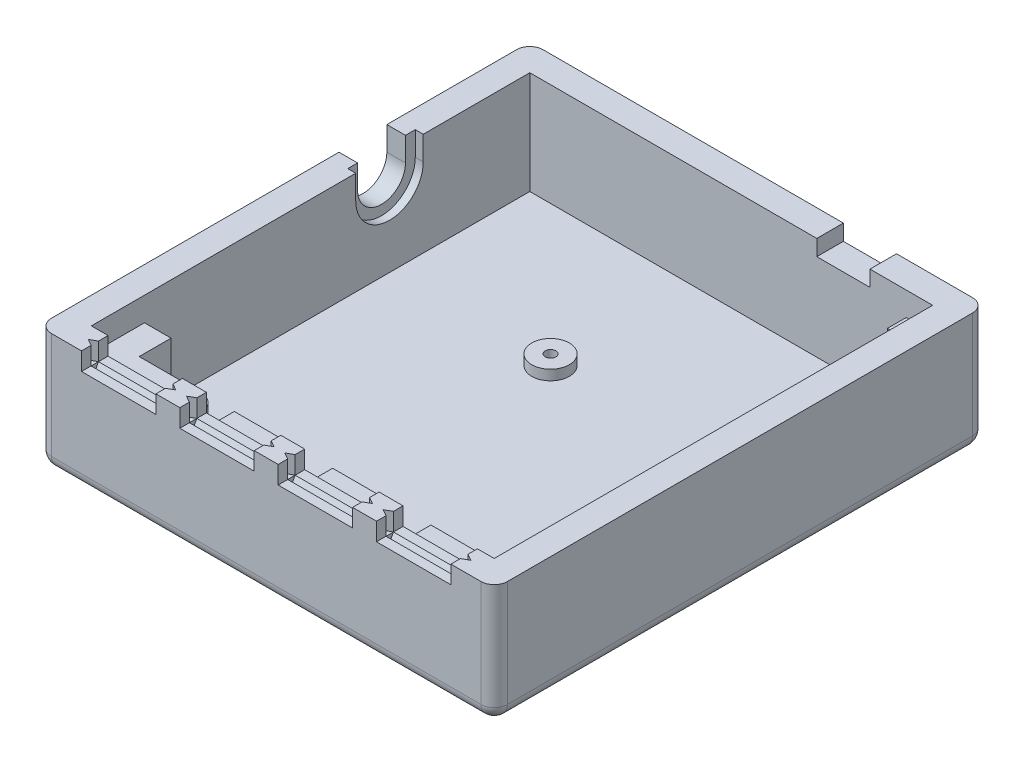
SolidWorks part; units mm, degrees
ref_plane "Front Plane" through (0, 0, 0) normal (0, 0, 1) x (1, 0, 0)
ref_plane "Top Plane" through (0, 0, 0) normal (0, 1, 0) x (1, 0, 0)
ref_plane "Right Plane" through (0, 0, 0) normal (1, 0, 0) x (0, 0, -1)
sketch "Sketch1" plane through (0, 0, 0) normal (0, 1, 0) x (1, 0, 0)
  line L0 (5, 4) -> (5, 10)
  line L1 (5, 10) -> (0, 10)
  line L2 (0, 10) -> (0, 82.5)
  line L3 (0, 82.5) -> (70.8, 82.5)
  line L4 (70.8, 82.5) -> (70.8, 79)
  line L5 (70.8, 79) -> (75.8, 79)
  line L6 (75.8, 79) -> (75.8, 4)
  line L7 (5, 4) -> (15.9, 4)
  line L8 (15.9, 4) -> (15.9, 0)
  line L9 (15.9, 0) -> (22.9, 0)
  line L10 (22.9, 0) -> (22.9, 4)
  line L11 (22.9, 4) -> (34.4, 4)
  line L12 (34.4, 4) -> (34.4, 0)
  line L13 (34.4, 0) -> (41.4, 0)
  line L14 (41.4, 0) -> (41.4, 4)
  line L15 (41.4, 4) -> (52.9, 4)
  line L16 (52.9, 4) -> (52.9, 0)
  line L17 (52.9, 0) -> (59.9, 0)
  line L18 (59.9, 0) -> (59.9, 4)
  line L19 (59.9, 4) -> (75.8, 4)
  line L20 (19.4, 27.0002) -> (19.4, -18.5168) construction
  line L21 (37.9, 24.8892) -> (37.9, -19.4403) construction
  line L22 (56.4, 24.8892) -> (56.4, -19.4529) construction
  line L23 (-5, 87.5) -> (-5, -5)
  line L24 (-5, -5) -> (80.8, -5)
  line L25 (80.8, -5) -> (80.8, 87.5)
  line L26 (80.8, 87.5) -> (-5, 87.5)
  dimension "D1" = 82.5
  dimension "D2" = 75.8
  dimension "D3" = 3.5
  dimension "D4" = 5
  dimension "D5" = 7
  dimension "D6" = 7
  dimension "D7" = 7
  dimension "D8" = 19.4
  dimension "D9" = 18.5
  dimension "D10" = 18.5
  dimension "D11" = 5
  dimension "D12" = 4
  dimension "D13" = 6
  dimension "D14" = 5
  dimension "D15" = 5
  dimension "D16" = 5
  dimension "D17" = 5
extrude "Boss-Extrude1" add sketch "Sketch1" along normal blind 14.859
sketch "Sketch2" plane through (0, 0, 0) normal (0, 1, 0) x (1, 0, 0)
  line L0 (-5, 87.5) -> (-5, -5) construction
  line L1 (-5, 87.5) -> (80.8, 87.5)
  line L2 (-5, 87.5) -> (-5, -5)
  line L3 (-5, -5) -> (80.8, -5)
  line L4 (80.8, 87.5) -> (80.8, -5)
  line L5 (80.8, 87.5) -> (-5, 87.5) construction
  line L6 (80.8, -5) -> (80.8, 87.5) construction
  line L7 (-5, -5) -> (80.8, -5) construction
  circle A0 centre (3.5, 13.5) radius 1
  circle A1 centre (19.4, 3.5) radius 1
  circle A2 centre (37.9, 3.5) radius 1
  circle A3 centre (56.4, 3.5) radius 1
  circle A4 centre (30.3, 56.1) radius 1
  circle A5 centre (71.8, 75.5) radius 1
  dimension "D3" = 2
  dimension "D1" = 3.5
  dimension "D2" = 13.5
  dimension "D4" = 19.4
  dimension "D5" = 18.5
  dimension "D6" = 18.5
  dimension "D7" = 3.5
  dimension "D8" = 56.1
  dimension "D9" = 30.3
  dimension "D10" = 71.8
  dimension "D11" = 75.5
extrude "Boss-Extrude2" add sketch "Sketch2" against normal blind 3.175
ref_plane "Plane1" through (0, 14.859, 0) normal (0, 1, 0) x (1, 0, 0)
sketch "Sketch4" plane through (0, 14.859, 0) normal (0, 1, 0) x (1, 0, 0)
  line L1 (0, 0) -> (75.8, 0)
  line L2 (0, 0) -> (0, 82.5)
  line L3 (0, 82.5) -> (75.8, 82.5)
  line L4 (75.8, 0) -> (75.8, 82.5)
  line L5 (-5, -5) -> (80.8, -5)
  line L6 (-5, -5) -> (-5, 87.5)
  line L7 (-5, 87.5) -> (80.8, 87.5)
  line L8 (80.8, -5) -> (80.8, 87.5)
  dimension "D1" = 82.5
  dimension "D2" = 75.8
  dimension "D3" = 5
  dimension "D4" = 5
  dimension "D5" = 5
  dimension "D6" = 5
extrude "Boss-Extrude3" add sketch "Sketch4" along normal blind 4.5
sketch "Sketch3" plane through (0, 0, 0) normal (1, 0, 0) x (0, 0, -1)
  line L0 (60.6, 14.859) -> (60.6, 19.359)
  line L1 (87.5, 19.359) -> (-5, 19.359) construction
  line L2 (51.6, 14.859) -> (51.6, 19.359)
  line L3 (60.6, 19.359) -> (51.6, 19.359)
  circle A0 centre (56.1, 14.859) radius 4.5 construction
  arc A1 (60.6, 14.859) -> (51.6, 14.859) centre (56.1, 14.859) cw
  dimension "D1" = 9
  dimension "D2" = 56.1
  dimension "D3" = 14.859
extrude "Cut-Extrude1" cut sketch "Sketch3" against normal through all
sketch "Sketch5" plane through (0, 0, 0) normal (0, 0, 1) x (1, 0, 0)
  line L1 (3.15, 24) -> (17.15, 24)
  line L2 (3.15, 24) -> (3.15, 16)
  line L3 (3.15, 16) -> (17.15, 16)
  line L4 (17.15, 24) -> (17.15, 16)
  line L5 (21.65, 24) -> (35.65, 24)
  line L6 (21.65, 24) -> (21.65, 16)
  line L7 (21.65, 16) -> (35.65, 16)
  line L8 (35.65, 24) -> (35.65, 16)
  line L9 (40.15, 24) -> (54.15, 24)
  line L10 (40.15, 24) -> (40.15, 16)
  line L11 (40.15, 16) -> (54.15, 16)
  line L12 (54.15, 24) -> (54.15, 16)
  line L13 (72.65, 24) -> (58.65, 24)
  line L14 (72.65, 24) -> (72.65, 16)
  line L15 (72.65, 16) -> (58.65, 16)
  line L16 (58.65, 24) -> (58.65, 16)
  point P16 (10.15, 16)
  point P17 (28.65, 16)
  point P18 (47.15, 16)
  point P19 (65.65, 16)
  dimension "D1" = 10.15
  dimension "D2" = 18.5
  dimension "D3" = 18.5
  dimension "D4" = 18.5
  dimension "D5" = 14
  dimension "D6" = 14
  dimension "D7" = 14
  dimension "D8" = 14
  dimension "D9" = 16
  dimension "D10" = 8
extrude "Cut-Extrude2" cut sketch "Sketch5" along normal through all
sketch "Sketch6" plane through (0, 0, 0) normal (0, 0, 1) x (1, 0, 0)
  line L1 (54, 16.383) -> (64, 16.383)
  line L4 (64, 16.383) -> (64, 22.383)
  line L5 (64, 22.383) -> (54, 22.383)
  line L6 (54, 22.383) -> (54, 16.383)
  point P0 (59, 16.383)
  dimension "D1" = 59
  dimension "D2" = 10
  dimension "D3" = 6
  dimension "D4" = 16.383
extrude "Cut-Extrude3" cut sketch "Sketch6" against normal through all
sketch "Sketch7" plane through (0, 0, 0) normal (0, 1, 0) x (1, 0, 0)
  line L0 (0, 13.5) -> (0, 10)
  line L1 (0, 51.6) -> (0, 0) construction
  line L2 (0, 10) -> (3.5, 10)
  line L3 (0, 10) -> (5, 10) construction
  line L4 (15.9, 3.5) -> (15.9, 0)
  line L5 (15.9, 4) -> (15.9, 0) construction
  line L6 (15.9, 0) -> (22.9, 0)
  line L7 (22.9, 0) -> (22.9, 3.5)
  line L8 (22.9, 0) -> (22.9, 4) construction
  line L9 (34.4, 3.5) -> (34.4, 0)
  line L10 (34.4, 4) -> (34.4, 0) construction
  line L11 (21.65, 0) -> (35.65, 0) construction
  line L12 (22.9, 0) -> (34.4, 0) construction
  line L13 (34.4, 0) -> (41.4, 0)
  line L14 (41.4, 0) -> (41.4, 3.5)
  line L15 (41.4, 0) -> (41.4, 4) construction
  line L16 (52.9, 3.5) -> (52.9, 0)
  line L17 (52.9, 4) -> (52.9, 0) construction
  line L18 (52.9, 0) -> (59.9, 0)
  line L19 (59.9, 0) -> (59.9, 3.5)
  line L20 (59.9, 0) -> (59.9, 4) construction
  line L21 (75.8, 79) -> (69.8635, 79)
  line L22 (75.8, 79) -> (70.8, 79) construction
  line L23 (75.8, 79) -> (75.8, 75.5)
  line L24 (75.8, 0) -> (75.8, 82.5) construction
  circle A0 centre (30.3, 56.1) radius 3.54
  circle A1 centre (30.3, 56.1) radius 1
  circle A2 centre (3.5, 13.5) radius 1
  arc A3 (0, 13.5) -> (3.5, 10) centre (3.5, 13.5) cw
  circle A4 centre (19.4, 3.5) radius 1
  arc A5 (15.9, 3.5) -> (22.9, 3.5) centre (19.4, 3.5) cw
  circle A6 centre (37.9, 3.5) radius 1
  arc A7 (34.4, 3.5) -> (41.4, 3.5) centre (37.9, 3.5) cw
  circle A8 centre (56.4, 3.5) radius 1
  arc A9 (52.9, 3.5) -> (59.9, 3.5) centre (56.4, 3.5) cw
  circle A10 centre (71.8, 75.5) radius 1
  arc A11 (75.8, 75.5) -> (69.8635, 79) centre (71.8, 75.5) cw
  dimension "D1" = 2.54
  dimension "D2" = 2
  dimension "D3" = 2
  dimension "D4" = 2
  dimension "D5" = 2
  dimension "D7" = 2
  dimension "D9" = 2
extrude "Boss-Extrude4" add sketch "Sketch7" along normal blind 1.9
fillet "Fillet1" radius 2.5 1 edges at (-5, 8.092, 5)
fillet "Fillet2" radius 2.5 1 edges at (80.8, 8.092, 5)
fillet "Fillet3" radius 2.5 1 edges at (80.8, 8.092, -87.5)
fillet "Fillet4" radius 2.5 1 edges at (-5, 8.092, -87.5)
fillet "Fillet5" radius 2.5 8 edges at (80.0678, -3.175, 4.2678) (37.9, -3.175, 5) (-4.2678, -3.175, 4.2678) (-5, -3.175, -41.25) (-4.2678, -3.175, -86.7678) (37.9, -3.175, -87.5) (80.0678, -3.175, -86.7678) (80.8, -3.175, -41.25)
sketch "Sketch8" plane through (0, 0, 0) normal (1, 0, 0) x (0, 0, -1)
  line L0 (62.45, 14.855) -> (62.45, 21.205)
  line L1 (49.75, 14.855) -> (49.75, 21.205)
  line L2 (49.75, 21.205) -> (62.45, 21.205)
  circle A0 centre (56.1, 14.855) radius 6.35 construction
  arc A1 (49.75, 14.855) -> (62.45, 14.855) centre (56.1, 14.855) ccw
  dimension "D3" = 12.7
  dimension "D1" = 56.1
  dimension "D2" = 14.855
extrude "Cut-Extrude4" cut sketch "Sketch8" against normal blind 1.5
ref_plane "Plane2" through (0, 19.359, 0) normal (0, 1, 0) x (1, 0, 0)
sketch "Sketch9" plane through (0, 19.359, 0) normal (0, 1, 0) x (1, 0, 0)
  line L0 (3.15, -5) -> (3.15, 0) construction
  line L1 (3.15, -1.8) -> (3.15, -3.2)
  line L2 (3.15, 0) -> (3.15, -5) construction
  line L3 (3.15, -3.2) -> (1.9, -2.5)
  line L4 (1.9, -2.5) -> (3.15, -1.8)
  line L5 (17.15, -1.8) -> (17.15, -3.2)
  line L6 (17.15, -5) -> (17.15, 0) construction
  line L7 (17.15, -3.2) -> (18.4, -2.5)
  line L8 (18.4, -2.5) -> (17.15, -1.8)
  line L9 (21.65, -1.8) -> (21.65, -3.2)
  line L10 (21.65, 0) -> (21.65, -5) construction
  line L11 (21.65, -3.2) -> (20.4, -2.5)
  line L12 (20.4, -2.5) -> (21.65, -1.8)
  line L13 (35.65, -1.8) -> (36.9, -2.5)
  line L14 (35.65, -5) -> (35.65, 0) construction
  line L15 (36.9, -2.5) -> (35.65, -3.2)
  line L16 (35.65, -5) -> (35.65, 0) construction
  line L17 (35.65, -3.2) -> (35.65, -1.8)
  line L18 (40.15, -1.8) -> (38.9, -2.5)
  line L19 (40.15, -5) -> (40.15, 0) construction
  line L20 (38.9, -2.5) -> (40.15, -3.2)
  line L21 (40.15, -3.2) -> (40.15, -1.8)
  line L22 (54.15, -1.8) -> (54.15, -3.2)
  line L23 (54.15, -5) -> (54.15, 0) construction
  line L24 (54.15, -3.2) -> (55.4, -2.5)
  line L25 (55.4, -2.5) -> (54.15, -1.8)
  line L26 (58.65, -1.8) -> (58.65, -3.2)
  line L27 (58.65, -5) -> (58.65, 0) construction
  line L28 (58.65, -3.2) -> (57.4, -2.5)
  line L29 (57.4, -2.5) -> (58.65, -1.8)
  line L30 (72.65, -1.8) -> (72.65, -3.2)
  line L31 (72.65, -5) -> (72.65, 0) construction
  line L32 (72.65, -5) -> (72.65, 0) construction
  line L33 (72.65, -3.2) -> (73.9, -2.5)
  line L34 (73.9, -2.5) -> (72.65, -1.8)
  point P0 (3.15, -2.5)
  dimension "D1" = 1.25
  dimension "D2" = 0.7
  dimension "D3" = 0.7
  dimension "D4" = 1.25
  dimension "D5" = 1.25
  dimension "D6" = 1.25
  dimension "D7" = 1.25
  dimension "D8" = 1.25
  dimension "D9" = 1.25
  dimension "D10" = 1.25
extrude "Cut-Extrude5" cut sketch "Sketch9" against normal blind 4
sketch "Sketch10" plane through (0, 0, 0) normal (1, 0, 0) x (0, 0, -1)
  line L0 (-3.2, 16) -> (-1.8, 16)
  line L1 (-1.8, 16) -> (-2.5, 14.7)
  line L2 (-2.5, 14.7) -> (-3.2, 16)
  line L3 (-2.5, 16) -> (-2.5, 14.7) construction
  point P4 (0, 0)
  dimension "D1" = 16
  dimension "D2" = 2.5
  dimension "D3" = 1.3
  dimension "D4" = 1.4
extrude "Cut-Extrude7" cut sketch "Sketch10" along normal blind 73.9
sketch "Sketch12" plane through (0, 0, 0) normal (0, 0, 1) x (1, 0, 0)
  line L1 (3.15, 16) -> (-1.351, 16)
  line L2 (3.15, 16) -> (3.15, 12)
  line L3 (3.15, 12) -> (-1.351, 12)
  line L4 (-1.351, 16) -> (-1.351, 12)
  line L5 (21.65, 16) -> (17.149, 16)
  line L6 (21.65, 16) -> (21.65, 12)
  line L7 (21.65, 12) -> (17.149, 12)
  line L8 (17.149, 16) -> (17.149, 12)
  line L9 (40.15, 16) -> (35.649, 16)
  line L10 (40.15, 16) -> (40.15, 12)
  line L11 (40.15, 12) -> (35.649, 12)
  line L12 (35.649, 16) -> (35.649, 12)
  line L13 (58.65, 16) -> (54.149, 16)
  line L14 (58.65, 16) -> (58.65, 12)
  line L15 (58.65, 12) -> (54.149, 12)
  line L16 (54.149, 16) -> (54.149, 12)
  line L17 (72.65, 16) -> (77.151, 16)
  line L18 (72.65, 16) -> (72.65, 12)
  line L19 (72.65, 12) -> (77.151, 12)
  line L20 (77.151, 16) -> (77.151, 12)
  dimension "D1" = 4
  dimension "D2" = 4.501
extrude "Boss-Extrude8" add sketch "Sketch12" along normal blind 5
